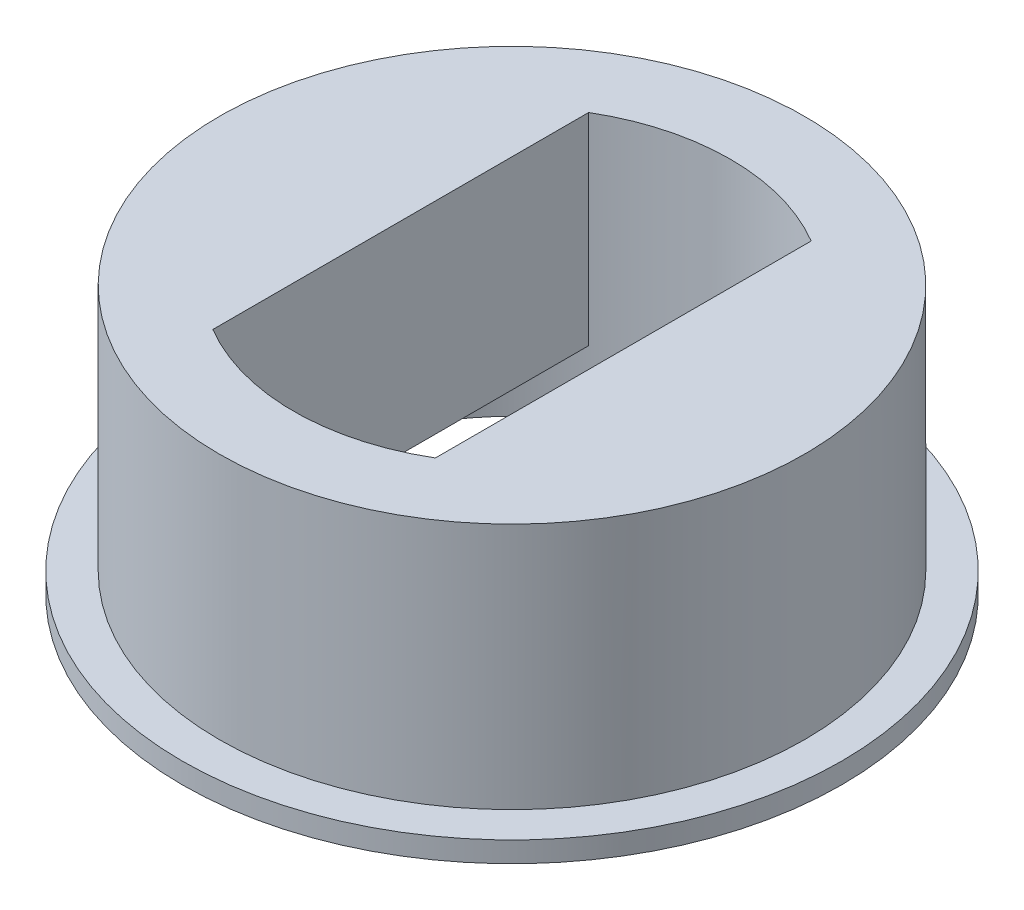
SolidWorks part; units mm, degrees
ref_plane "Front Plane" through (0, 0, 0) normal (0, 0, 1) x (1, 0, 0)
ref_plane "Top Plane" through (0, 0, 0) normal (0, 1, 0) x (1, 0, 0)
ref_plane "Right Plane" through (0, 0, 0) normal (1, 0, 0) x (0, 0, -1)
sketch "Sketch1" plane through (0, 0, 0) normal (0, 1, 0) x (1, 0, 0)
  circle A0 centre (0, 0) radius 7
extrude "Boss-Extrude1" add sketch "Sketch1" along normal blind 7
sketch "Sketch2" plane through (0, 0, 0) normal (0, -1, 0) x (1, 0, 0)
  line L0 (-2.7, 4.3371) -> (2.7, 4.3371)
  line L1 (-2.7, 4.3371) -> (-2.7, -4.3371)
  line L2 (2.7, 4.3371) -> (2.7, -4.3371)
  line L3 (-2.7, -4.3371) -> (2.7, -4.3371)
  line L4 (-2.7, 4.3371) -> (2.7, -4.3371) construction
  line L5 (2.7, 4.3371) -> (-2.7, -4.3371) construction
  circle A0 centre (0, 0) radius 2.7
extrude "Cut-Extrude2" cut sketch "Sketch2" against normal blind 10 contours A0 L2 L0 L1 | A0 L1 L3 L2 | A0
sketch "Sketch3" plane through (0, 0, 0) normal (0, -1, 0) x (1, 0, 0)
  line L0 (-2.7, -4.3371) -> (2.7, -4.3371) construction
  line L1 (2.7, 4.3371) -> (2.7, -4.3371) construction
  line L2 (-2.7, 4.3371) -> (2.7, 4.3371) construction
  line L3 (-2.7, 4.3371) -> (-2.7, -4.3371) construction
  line L4 (-2.7, -4.3371) -> (2.7, -4.3371)
  line L5 (2.7, 4.3371) -> (2.7, -4.3371)
  line L6 (-2.7, 4.3371) -> (2.7, 4.3371)
  line L7 (-2.7, 4.3371) -> (-2.7, -4.3371)
  circle A0 centre (0, 0) radius 8
extrude "Boss-Extrude2" add sketch "Sketch3" against normal blind 1
sketch "Sketch4" plane through (0, 0, 0) normal (0, -1, 0) x (1, 0, 0)
  circle A1 centre (0, 0) radius 8
  circle A2 centre (0, 0) radius 8
  dimension "D1" = 0
extrude "Cut-Extrude3" cut sketch "Sketch4" against normal blind 0.5
sketch "Sketch5" plane through (0, 7, 0) normal (0, 1, 0) x (1, 0, 0)
  line L0 (-2.7, 4.3371) -> (-2.7, -4.3371) construction
  line L1 (2.7, 4.3371) -> (-2.7, 4.3371) construction
  line L2 (2.7, 4.3371) -> (2.7, -4.3371) construction
  line L3 (2.7, -4.3371) -> (-2.7, -4.3371) construction
  line L4 (-2.7, 4.3371) -> (-2.7, -4.3371)
  line L5 (2.7, 4.3371) -> (-2.7, 4.3371)
  line L6 (2.7, 4.3371) -> (2.7, -4.3371)
  line L7 (2.7, -4.3371) -> (-2.7, -4.3371)
  circle A0 centre (0, 0) radius 7.1
extrude "Boss-Extrude3" add sketch "Sketch5" against normal up to surface (6 mm away) up to face at (0, 1, -8)
sketch "Sketch6" plane through (0, 0.5, 0) normal (0, -1, 0) x (1, 0, 0)
  circle A1 centre (0, 0) radius 5.1088
extrude "Cut-Extrude4" cut sketch "Sketch6" against normal blind 1.1
sketch "Sketch8" plane through (0, 1.6, 0) normal (0, -1, 0) x (1, 0, 0)
  line L0 (-2.7, 4.3371) -> (2.7, 4.3371) construction
  line L1 (2.7, -4.3371) -> (-2.7, -4.3371) construction
  line L2 (-2.7, 4.3371) -> (2.7, 4.3371)
  line L3 (2.7, -4.3371) -> (-2.7, -4.3371)
  arc A0 (2.7, 4.3371) -> (-2.7, 4.3371) centre (0, 0) ccw construction
  arc A1 (-2.7, -4.3371) -> (2.7, -4.3371) centre (0, 0) ccw construction
  arc A2 (2.7, 4.3371) -> (-2.7, 4.3371) centre (0, 0) ccw
  arc A3 (-2.7, -4.3371) -> (2.7, -4.3371) centre (0, 0) ccw
extrude "Cut-Extrude5" cut sketch "Sketch8" against normal blind 10.1
sketch "Sketch9" plane through (0, 0.5, 0) normal (0, -1, 0) x (1, 0, 0)
  circle A0 centre (0, 0) radius 5.2986
extrude "Cut-Extrude6" cut sketch "Sketch9" against normal blind 1.6
sketch "Sketch10" plane through (0, 2.1, 0) normal (0, -1, 0) x (1, 0, 0)
  line L0 (-2.7, -4.3371) -> (-2.7, 4.3371)
  line L1 (-2.7, 4.3371) -> (-2.7, 5.6305)
  line L2 (-2.7, 5.6305) -> (2.7, -4.3371)
  line L3 (2.7, -4.3371) -> (2.7, 4.3371)
  line L4 (2.7, 4.3371) -> (2.7, 5.4209)
  line L5 (2.7, 5.4209) -> (-2.7, -6.1547)
  line L6 (-2.7, -6.1547) -> (-2.7, -4.3371)
  line L7 (-2.7, -6.1547) -> (2.7, -6.1547)
  line L8 (2.7, -6.1547) -> (2.7, -4.3371)
  circle A0 centre (0, 0) radius 5.2986 construction
  circle A1 centre (0, 0) radius 5.2986
  circle M2 centre (0, 0) radius 5.2986
  arc M3 (-2.7, 4.3371) -> (2.7, 4.3371) centre (0, 0) cw
  arc M5 (2.7, -4.3371) -> (-2.7, -4.3371) centre (0, 0) cw
extrude "Cut-Extrude7" cut sketch "Sketch10" against normal blind 10.6 contours L5 L2 M2 M3 | L2 L1 M2 M3 | L6 L5 M2 M5 | L8 L5 M2 M5 | L5 L4 M2 M3 | A1
